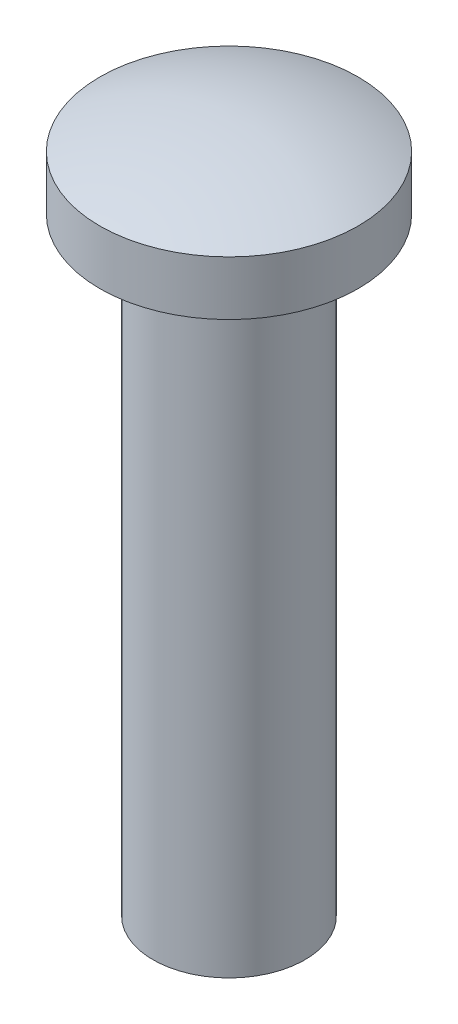
SolidWorks part; units mm, degrees
ref_plane "前基準面" through (0, 0, 0) normal (0, 0, 1) x (1, 0, 0)
ref_plane "上基準面" through (0, 0, 0) normal (0, 1, 0) x (1, 0, 0)
ref_plane "右基準面" through (0, 0, 0) normal (1, 0, 0) x (0, 0, -1)
sketch "草圖1" plane through (0, 0, 0) normal (0, 0, 1) x (1, 0, 0)
  line L0 (0, 0) -> (0, 4.5382)
  line L1 (-0.85, 4.3572) -> (-0.85, 4)
  line L2 (-0.85, 4) -> (-0.5, 4)
  line L3 (-0.5, 4) -> (-0.5, 0)
  line L4 (-0.5, 0) -> (0, 0)
  arc A0 (0, 4.5382) -> (-0.85, 4.3572) centre (0, 2.4521) ccw
  dimension "D4" = 2.0862
  dimension "D1" = 0.5
  dimension "D2" = 4
  dimension "D3" = 0.85
revolve "旋轉1" add sketch "草圖1" angle 360 about L0
cosmetic thread "裝飾螺紋線1" parameters "D1"=1, "D2"=0.711
